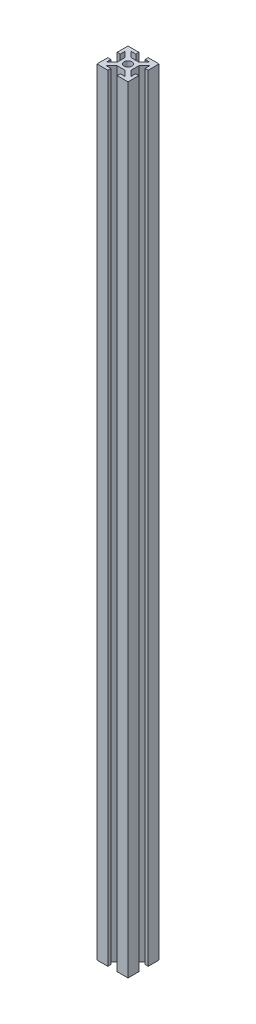
SolidWorks part; units mm, degrees
ref_plane "Alzado" through (0, 0, 0) normal (0, 0, 1) x (1, 0, 0)
ref_plane "Planta" through (0, 0, 0) normal (0, 1, 0) x (1, 0, 0)
ref_plane "Vista lateral" through (0, 0, 0) normal (1, 0, 0) x (0, 0, -1)
sketch "Croquis1" plane through (0, 0, 0) normal (0, 1, 0) x (1, 0, 0)
  line L0 (3, 10) -> (3, 8)
  line L1 (-10, 3) -> (-10, 10)
  line L2 (-8, 3) -> (-10, 3)
  line L3 (10, 10) -> (3, 10)
  line L4 (-8, 6) -> (-8, 3)
  line L5 (10, -10) -> (-10, 10) construction
  line L6 (10, 10) -> (-10, -10) construction
  line L7 (3, 8) -> (6, 8)
  line L8 (6, 8) -> (2.5, 4.5)
  line L9 (2.5, 4.5) -> (-2.5, 4.5)
  line L10 (-2.5, 4.5) -> (-6, 8)
  line L11 (-6, 8) -> (-3, 8)
  line L12 (-3, 8) -> (-3, 10)
  line L13 (-4.5, 2.5) -> (-8, 6)
  line L14 (-3, 10) -> (-10, 10)
  line L15 (-4.5, -2.5) -> (-4.5, 2.5)
  line L16 (-8, -6) -> (-4.5, -2.5)
  line L17 (-8, -3) -> (-8, -6)
  line L18 (-10, -10) -> (-10, -3)
  line L19 (-10, -3) -> (-8, -3)
  line L20 (-3, -10) -> (-3, -8)
  line L21 (-10, -10) -> (-3, -10)
  line L22 (-3, -8) -> (-6, -8)
  line L23 (-6, -8) -> (-2.5, -4.5)
  line L24 (-2.5, -4.5) -> (2.5, -4.5)
  line L25 (10, -3) -> (10, -10)
  line L26 (2.5, -4.5) -> (6, -8)
  line L27 (8, -3) -> (10, -3)
  line L28 (8, -6) -> (8, -3)
  line L29 (4.5, -2.5) -> (8, -6)
  line L30 (4.5, 2.5) -> (4.5, -2.5)
  line L31 (8, 6) -> (4.5, 2.5)
  line L32 (8, 3) -> (8, 6)
  line L33 (6, -8) -> (3, -8)
  line L34 (10, 10) -> (10, 3)
  line L35 (3, -8) -> (3, -10)
  line L36 (3, -10) -> (10, -10)
  line L37 (10, 3) -> (8, 3)
  circle A0 centre (0, 0) radius 2.5
  point P0 (0, 0)
  point P7 (3, 9)
  point P15 (-3, 9)
  dimension "D3" = 5
  dimension "D1" = 20
  dimension "D4" = 6
  dimension "D5" = 12
  dimension "D6" = 2
  dimension "D7" = 5
extrude "Saliente-Extruir1" add sketch "Croquis1" along normal blind 500
